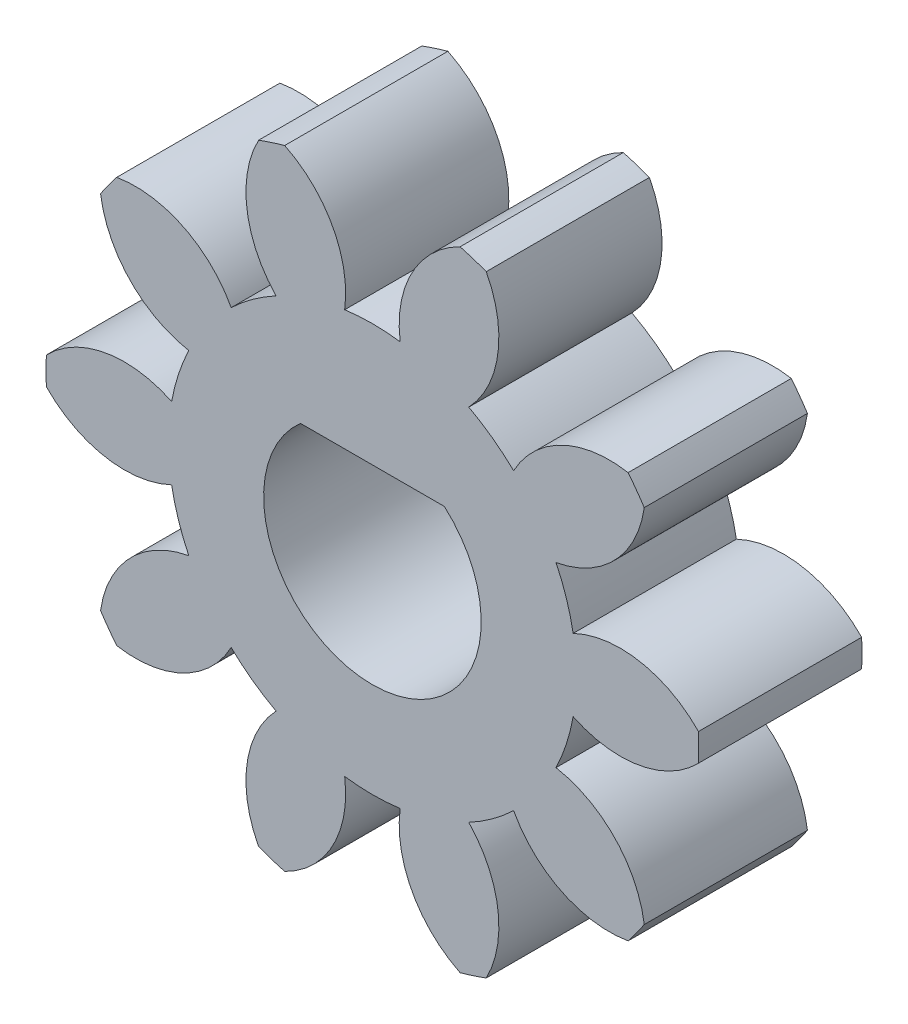
SolidWorks part; units mm, degrees
ref_plane "Front Plane" through (0, 0, 0) normal (0, 0, 1) x (1, 0, 0)
ref_plane "Top Plane" through (0, 0, 0) normal (0, 1, 0) x (1, 0, 0)
ref_plane "Right Plane" through (0, 0, 0) normal (1, 0, 0) x (0, 0, -1)
sketch "Sketch1" plane through (0, 0, 0) normal (0, 0, 1) x (1, 0, 0)
  circle A0 centre (0, 0) radius 6
  dimension "D1" = 12
extrude "Boss-Extrude1" add sketch "Sketch1" along normal blind 3
sketch "Sketch2" plane through (0, 0, 3) normal (0, 0, 1) x (1, 0, 0)
  line L0 (0, 0) -> (0, 29.2185) construction
  line L1 (0, 0) -> (-7.1036, 21.8626) construction
  line L2 (-0.7385, 4.9452) -> (-1.5239, 4.69) construction
  circle A0 centre (0, 0) radius 4.6985 construction
  circle A1 centre (0, 0) radius 5 construction
  circle A2 centre (0, 0) radius 3.75 construction
  arc A3 (-1.6122, 5.7793) -> (-0.51, 3.7152) centre (-2.4919, 3.9832) cw
  circle A4 centre (0, 0) radius 6 construction
  arc A5 (1.6122, 5.7793) -> (0.51, 3.7152) centre (2.4919, 3.9832) ccw
  arc A6 (-1.6122, 5.7793) -> (1.6122, 5.7793) centre (0, 0) cw
  arc A7 (-0.51, 3.7152) -> (0.51, 3.7152) centre (0, 0) cw
  dimension "D3" = 10
  dimension "D2" = 9.3969
  dimension "D1" = 7.5
  dimension "D5" = 2
  dimension "D4" = 18
  dimension "D6" = 0.7854
extrude "Cut-Extrude1" cut sketch "Sketch2" against normal through all
pattern_circular "CirPattern1" count 10 over 360 about axis through (0, 0, 0) along (0, 0, 1) of "Cut-Extrude1"
sketch "Sketch3" plane through (0, 0, 3) normal (0, 0, 1) x (1, 0, 0)
  line L3 (0, -19.3707) -> (0, 19.6934) construction
  line L4 (-2.1948, 4.712) -> (-2.1948, 10.712)
  line L6 (-16.5083, 8.819) -> (17.3222, -10.7131) construction
  line L7 (16.1333, 9.3146) -> (-17.6973, -10.2175) construction
  line L8 (-8.891, 6.846) -> (-3.6948, 3.846)
  arc A0 (-2.1948, 4.712) -> (-3.6948, 3.846) centre (-3.1948, 4.712) cw
  arc A1 (-9.391, 7.712) -> (-8.891, 6.846) centre (-8.391, 7.712) ccw
  arc A2 (-2.1948, 10.712) -> (-2.6948, 11.578) centre (-3.1948, 10.712) ccw
  arc A3 (-2.6948, 11.578) -> (-9.391, 7.712) centre (-0.352, -0.2119) ccw
  dimension "D3" = 1
  dimension "D1" = 60
  dimension "D2" = 60
  dimension "D4" = 6
extrude "Cut-Extrude2" [suppressed] cut sketch "Sketch3" against normal through all
pattern_circular "CirPattern2" [suppressed] count 6 over 360
sketch "Sketch4" plane through (0, 0, 3) normal (0, 0, 1) x (1, 0, 0)
  line L0 (-1.3229, 1.5) -> (1.3229, 1.5)
  arc A0 (-1.3229, 1.5) -> (1.3229, 1.5) centre (0, 0) ccw
  dimension "D1" = 4
  dimension "D2" = 1.5
extrude "Cut-Extrude3" cut sketch "Sketch4" against normal through all
equation "\"module\"= 1.0"
equation "\"teeth\"= 10"
equation "\"pressureAngle\"= 20deg"
equation "\"gearThickness\"= 3mm"
equation "\"addendumFactor\"= 1"
equation "\"dedendumFactor\"= 1.25"
equation "\"pitch\"= 1 / \"module\""
equation "\"pitchDiameter\"= \"teeth\" / \"pitch\""
equation "\"addendum\"= \"addendumFactor\" / \"pitch\""
equation "\"dedendum\"= \"dedendumFactor\" / \"pitch\""
equation "\"D1@Boss-Extrude1\"=\"gearThickness\""
equation "\"D1@Sketch1\"=\"pitchDiameter\"+2*\"addendum\""
equation "\"D3@Sketch2\"=\"pitchDiameter\""
equation "\"D2@Sketch2\"=\"pitchDiameter\"*cos( \"pressureAngle\")"
equation "\"D1@Sketch2\"=\"pitchDiameter\"-2*\"dedendum\""
equation "\"D4@Sketch2\"=180/\"teeth\""
equation "\"D5@Sketch2\"=\"pitchDiameter\"/5"
equation "\"D6@Sketch2\"=PI/2/\"pitch\"/2"
equation "\"D1@CirPattern1\"=\"teeth\""
